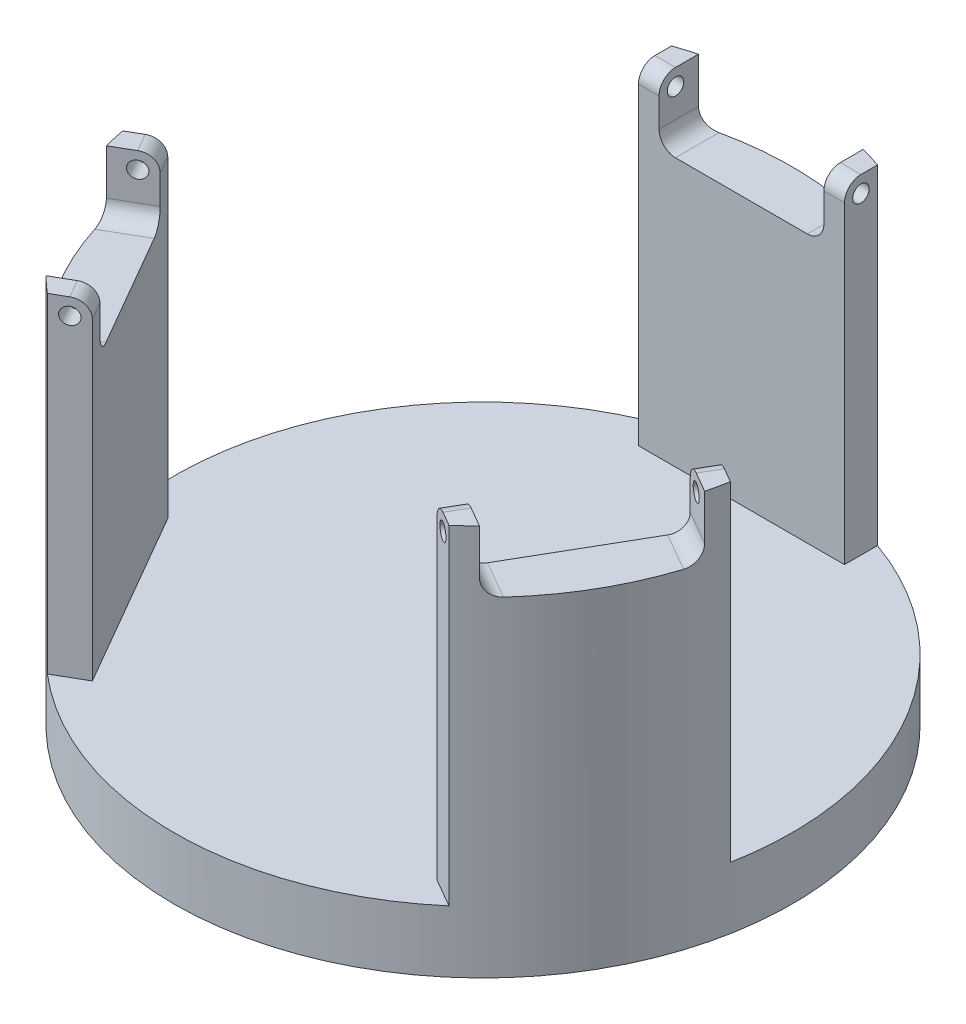
SolidWorks part; units mm, degrees
ref_plane "Front Plane" through (0, 0, 0) normal (0, 0, 1) x (1, 0, 0)
ref_plane "Top Plane" through (0, 0, 0) normal (0, 1, 0) x (1, 0, 0)
ref_plane "Right Plane" through (0, 0, 0) normal (1, 0, 0) x (0, 0, -1)
sketch "Sketch1" plane through (0, 0, 0) normal (0, 1, 0) x (1, 0, 0)
  circle A0 centre (0, 0) radius 75
  dimension "D1" = 150
extrude "Boss-Extrude1" add sketch "Sketch1" along normal blind 15
sketch "Sketch2" plane through (0, 15, 0) normal (0, 1, 0) x (1, 0, 0)
  line L2 (-25, 70.7107) -> (-25, 62.7107)
  line L3 (-25, 62.7107) -> (25, 62.7107)
  line L4 (25, 70.7107) -> (25, 62.7107)
  circle A0 centre (0, 0) radius 75 construction
  arc A1 (-25, 70.7107) -> (25, 70.7107) centre (0, 0) cw
  point P7 (0, 62.7107)
  dimension "D1" = 50
  dimension "D2" = 50
  dimension "D3" = 8
extrude "Boss-Extrude2" add sketch "Sketch2" along normal blind 80
sketch "Sketch3" plane through (0, 95, 0) normal (0, 1, 0) x (1, 0, 0)
  line L0 (-25, 62.7107) -> (25, 62.7107) construction
  line L2 (-20, 72.2842) -> (-20, 62.7107)
  line L3 (-20, 62.7107) -> (20, 62.7107)
  line L4 (20, 72.2842) -> (20, 62.7107)
  arc A0 (25, 70.7107) -> (-25, 70.7107) centre (0, 0) ccw construction
  arc A1 (-20, 72.2842) -> (20, 72.2842) centre (0, 0) cw
  point P11 (0, 62.7107)
  dimension "D1" = 40
extrude "Cut-Extrude1" cut sketch "Sketch3" against normal blind 15
hole_wizard "Ø4.0 mm Dowel Holes1" positions "Sketch4" profile "Sketch5" hole size "Ø4.0" standard "ISO" end condition through all
sketch "Sketch4" plane through (25, 0, 0) normal (1, 0, 0) x (0, 0, -1)
  line L0 (62.7107, 95) -> (62.7107, 15) construction
  line L1 (62.7107, 95) -> (70.7107, 95) construction
  point P0 (66.7107, 91)
  dimension "D1" = 4
  dimension "D2" = 4
sketch "Sketch5" plane through (25, 91, -66.7107) normal (0, 1, 0) x (0, 0, -1)
  line L0 (0, 0) -> (0, 100)
  line L1 (0, 100) -> (2, 100)
  line L2 (2, 100) -> (2, 0)
  line L5 (2, 0) -> (0, 0)
  line L11 (0, -6.35) -> (0, 107.95) construction
  dimension "Thru Hole Dia." = 4
  dimension "Thru Hole Depth" = 100
fillet "Fillet1" radius 4 2 edges at (-22.5, 95, -62.7107) (22.5, 95, -62.7107)
fillet "Fillet2" radius 4 2 edges at (-20, 80, -67.4974) (20, 80, -67.4974)
pattern_circular "CirPattern1" count 3 over 360 about axis through (0, 0, 0) along (0, 1, 0) of "Boss-Extrude2", "Cut-Extrude1", "Ø4.0 mm Dowel Holes1", "Fillet1", "Fillet2"
